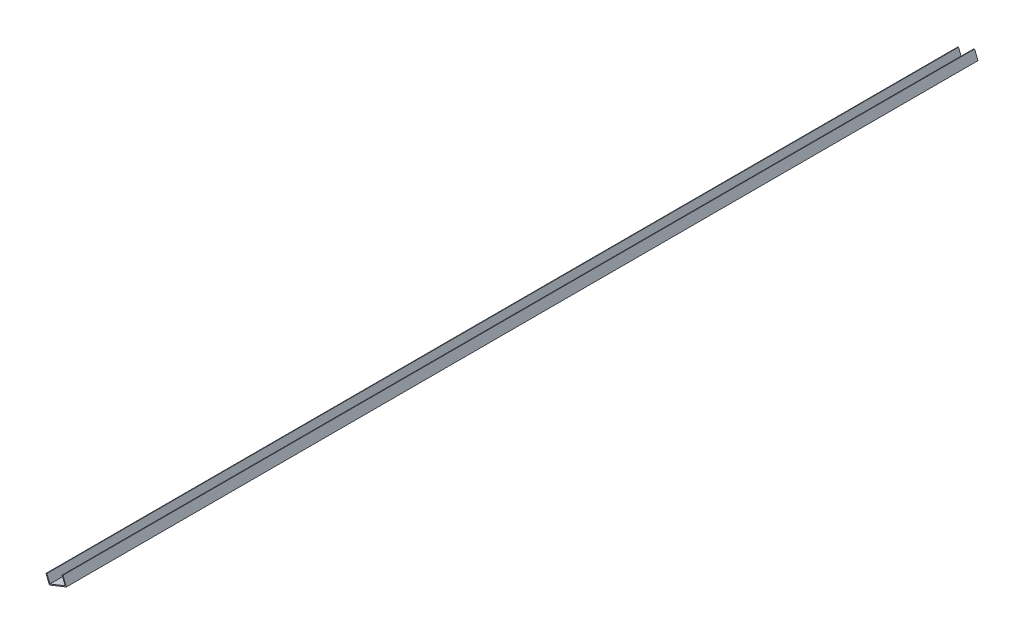
SolidWorks part; units mm, degrees
ref_plane "前视基准面" through (0, 0, 0) normal (0, 0, 1) x (1, 0, 0)
ref_plane "上视基准面" through (0, 0, 0) normal (0, 1, 0) x (1, 0, 0)
ref_plane "右视基准面" through (0, 0, 0) normal (1, 0, 0) x (0, 0, -1)
sketch "草图1" plane through (0, 0, 0) normal (0, 0, 1) x (1, 0, 0)
  line L1 (6761.5251, 10636.9025) -> (6778.2972, 10595.1449)
  line L2 (6778.2972, 10595.1449) -> (6861.8124, 10628.689)
  line L5 (6775.521, 10588.6416) -> (6756.8854, 10635.0389)
  line L6 (6756.8854, 10635.0389) -> (6761.5251, 10636.9025)
  line L11 (6845.0404, 10670.4466) -> (6849.6801, 10672.3101)
  line L12 (6849.6801, 10672.3101) -> (6868.3157, 10625.9128)
  line L13 (6849.6801, 10672.3101) -> (6845.0404, 10670.4466)
  line L14 (6845.0404, 10670.4466) -> (6861.8124, 10628.689)
  line L15 (6775.521, 10588.6416) -> (6868.3157, 10625.9128)
  dimension "D3" = 50
  dimension "D4" = 5
  dimension "D5" = 5
extrude "凸台-拉伸1" add sketch "草图1" along normal blind 5000 contours L5 L15 L12 L11 L14 L2 L1 L6
